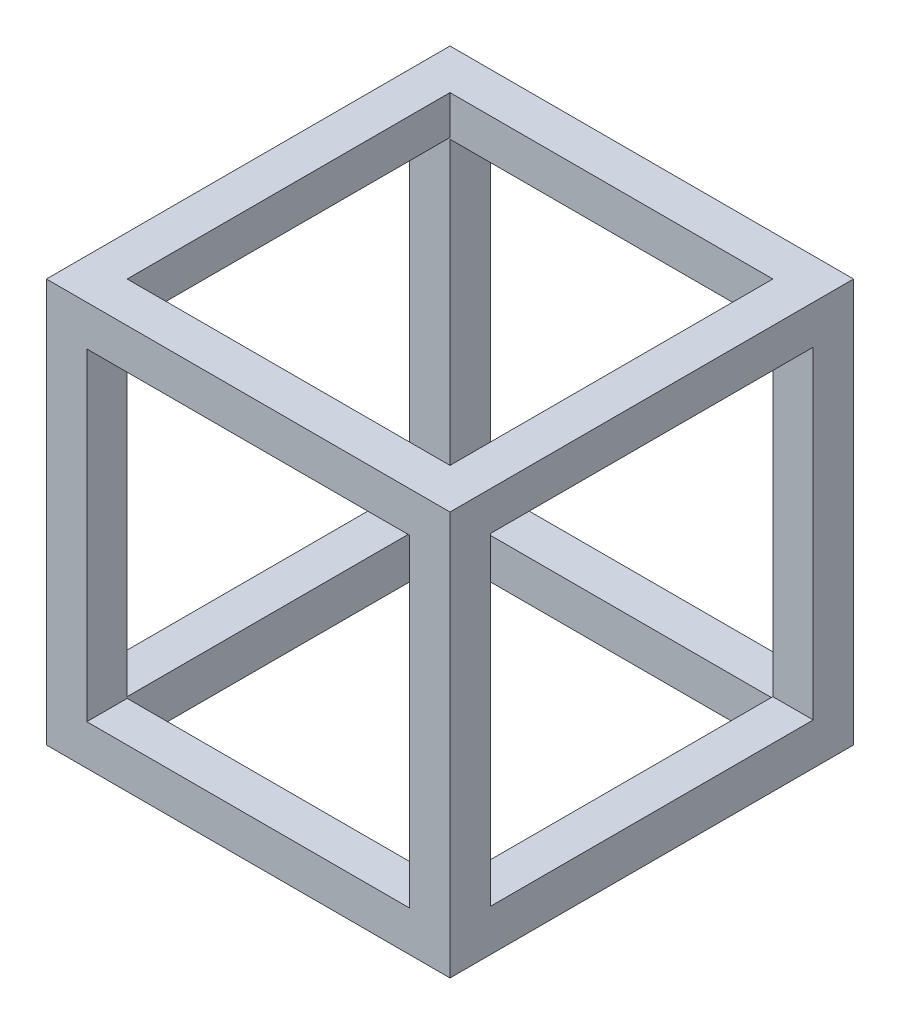
SolidWorks part; units mm, degrees
ref_plane "Front Plane" through (0, 0, 0) normal (0, 0, 1) x (1, 0, 0)
ref_plane "Top Plane" through (0, 0, 0) normal (0, 1, 0) x (1, 0, 0)
ref_plane "Right Plane" through (0, 0, 0) normal (1, 0, 0) x (0, 0, -1)
sketch "Sketch1" plane through (0, 0, 0) normal (0, 1, 0) x (1, 0, 0)
  line L1 (-0.5, -0.5) -> (0.5, -0.5)
  line L2 (-0.5, -0.5) -> (-0.5, 0.5)
  line L3 (-0.5, 0.5) -> (0.5, 0.5)
  line L4 (0.5, -0.5) -> (0.5, 0.5)
  line L5 (-0.5, -0.5) -> (0.5, 0.5) construction
  line L6 (-0.5, 0.5) -> (0.5, -0.5) construction
  point P0 (0, 0)
  point P5 (0, 0)
extrude "Boss-Extrude1" add sketch "Sketch1" along normal blind 1 contours L2 L3 L4 L1
sketch "Sketch2" plane through (0.5, 0, 0) normal (1, 0, 0) x (0, 0, -1)
  line L0 (0, 0) -> (0, 1) construction
  line L1 (-0.5, 0.5) -> (0.5, 0.5) construction
  line L5 (-0.4, 0.1037) -> (0.4, 0.1037)
  line L6 (-0.4, 0.1037) -> (-0.4, 0.9037)
  line L7 (-0.4, 0.9037) -> (0.4, 0.9037)
  line L8 (0.4, 0.1037) -> (0.4, 0.9037)
  line L9 (-0.4, 0.1037) -> (0.4, 0.9037) construction
  line L10 (-0.4, 0.9037) -> (0.4, 0.1037) construction
  point P2 (0, 0.5037)
extrude "Cut-Extrude2" cut sketch "Sketch2" against normal through all
sketch "Sketch3" plane through (0, 0, 0.5) normal (0, 0, 1) x (1, 0, 0)
  line L0 (-0.5, 0.5) -> (0.5, 0.5) construction
  line L3 (0, 1) -> (0, 0) construction
  line L6 (-0.4, 0.1) -> (0.4, 0.1)
  line L7 (-0.4, 0.1) -> (-0.4, 0.9)
  line L8 (-0.4, 0.9) -> (0.4, 0.9)
  line L9 (0.4, 0.1) -> (0.4, 0.9)
  line L10 (-0.4, 0.1) -> (0.4, 0.9) construction
  line L11 (-0.4, 0.9) -> (0.4, 0.1) construction
  point P2 (0, 0.5)
  point P8 (0, 0)
  point P10 (0, 0)
  point P11 (0, 0)
extrude "Cut-Extrude3" cut sketch "Sketch3" against normal through all
sketch "Sketch4" plane through (0, 1, 0) normal (0, 1, 0) x (1, 0, 0)
  line L1 (-0.4, -0.4) -> (0.4, -0.4)
  line L2 (-0.4, -0.4) -> (-0.4, 0.4)
  line L3 (-0.4, 0.4) -> (0.4, 0.4)
  line L4 (0.4, -0.4) -> (0.4, 0.4)
  line L5 (-0.4, -0.4) -> (0.4, 0.4) construction
  line L6 (-0.4, 0.4) -> (0.4, -0.4) construction
  point P0 (0, 0)
extrude "Cut-Extrude4" cut sketch "Sketch4" against normal through all
